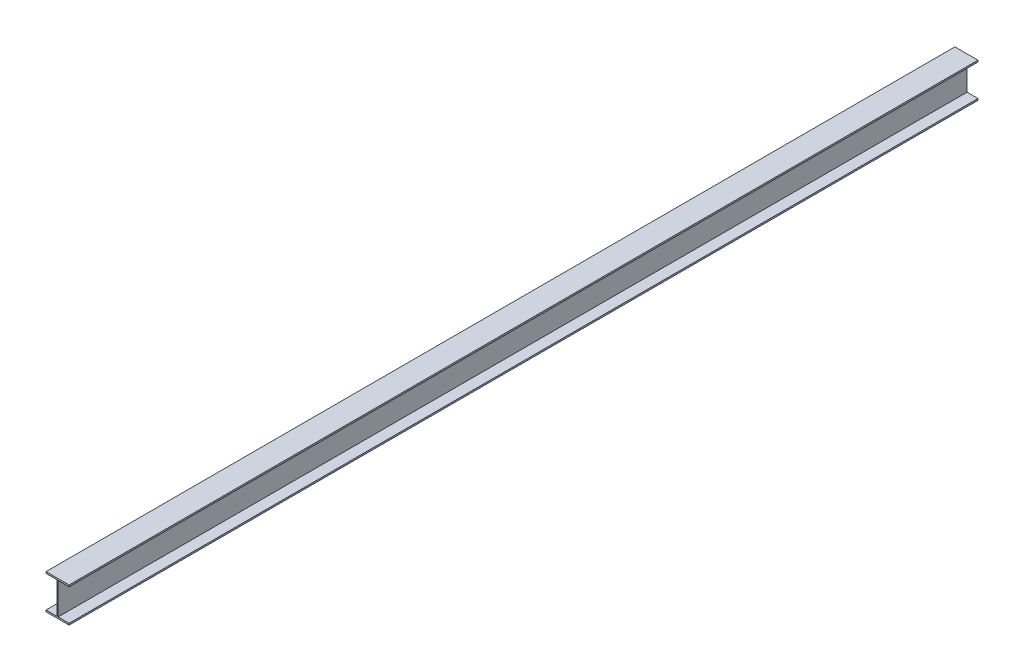
SolidWorks part; units mm, degrees
material "ASTM A992 Steel"
ref_plane "Front" through (0, 0, 0) normal (0, 0, 1) x (1, 0, 0)
ref_plane "Top" through (0, 0, 0) normal (0, 1, 0) x (1, 0, 0)
ref_plane "Right" through (0, 0, 0) normal (1, 0, 0) x (0, 0, -1)
sketch "Sketch1" plane through (0, 0, 0) normal (0, 0, 1) x (1, 0, 0)
  line L0 (0, -0.0002) -> (101.6, -0.0002)
  line L1 (101.6, -0.0002) -> (101.6, -7.1122)
  line L2 (101.6, -7.1122) -> (53.408, -7.1122)
  line L3 (53.408, -7.1122) -> (53.408, -146.0502)
  line L4 (53.408, -146.0502) -> (101.6, -146.0502)
  line L5 (101.6, -146.0502) -> (101.6, -153.1622)
  line L6 (101.6, -153.1622) -> (0, -153.1622)
  line L7 (0, -153.1622) -> (0, -146.0502)
  line L8 (0, -146.0502) -> (47.566, -146.0502)
  line L9 (47.566, -146.0502) -> (47.566, -7.1122)
  line L10 (47.566, -7.1122) -> (0, -7.1122)
  line L11 (0, -7.1122) -> (0, -0.0002)
  line L12 (50.8, -0.0002) -> (50.8, -153.1622) construction
  dimension "D1" = 5.842
  dimension "D2" = 7.112
  dimension "D3" = 7.112
  dimension "D4" = 7.112
  dimension "D5" = 153.162
  dimension "D6" = 50.8
  dimension "D7" = 50.8
  dimension "D8" = 47.566
extrude "Boss-Extrude1" add sketch "Sketch1" along normal blind 4000
sketch "Sketch2" plane through (0, -153.1622, 0) normal (0, -1, 0) x (1, 0, 0)
  line L2 (101.6, 4000) -> (101.6, 0) construction
  line L5 (101.6, 2000) -> (101.6, 2152.4)
  line L6 (101.6, 2152.4) -> (-229.7319, 2152.4)
  line L7 (-229.7319, 2000) -> (-229.7319, 2152.4)
  line L9 (101.6, 2000) -> (101.6, 1847.6)
  line L10 (101.6, 1847.6) -> (-229.7319, 1847.6)
  line L11 (-229.7319, 2000) -> (-229.7319, 1847.6)
  point P0 (101.6, 2000)
  dimension "D1" = 152.4
  dimension "D2" = 152.4
split line "Split Line1"
